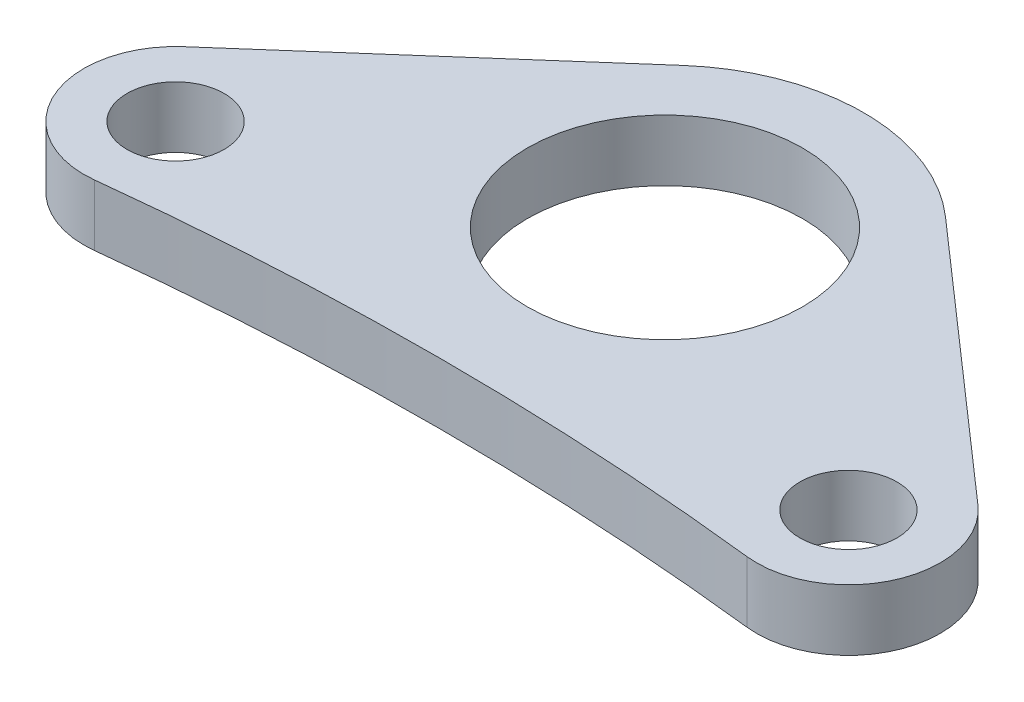
SolidWorks part; units mm, degrees
material "Plain Carbon Steel"
ref_plane "Front Plane" through (0, 0, 0) normal (0, 0, 1) x (1, 0, 0)
ref_plane "Top Plane" through (0, 0, 0) normal (0, 1, 0) x (1, 0, 0)
ref_plane "Right Plane" through (0, 0, 0) normal (1, 0, 0) x (0, 0, -1)
sketch "Sketch1" plane through (0, 0, 0) normal (0, 1, 0) x (1, 0, 0)
  line L0 (-41.2092, -8.7172) -> (-13.6158, 15.5086)
  line L1 (13.6158, 15.5086) -> (41.2092, -8.7172)
  circle A0 centre (0, 0) radius 14.2875
  arc A1 (-33.858, -25.3401) -> (-41.2092, -8.7172) centre (-34.925, -15.875) cw
  arc A2 (33.858, -25.3401) -> (41.2092, -8.7172) centre (34.925, -15.875) ccw
  arc A3 (-33.858, -25.3401) -> (33.858, -25.3401) centre (0, -325.6977) cw
  arc A4 (-13.6158, 15.5086) -> (13.6158, 15.5086) centre (0, 0) cw
  point P3 (-34.925, -15.875)
  point P4 (34.925, -15.875)
  dimension "D4" = 28.575
  dimension "D5" = 302.26
  dimension "D6" = 9.525
  dimension "D7" = 6.35
  dimension "D8" = 9.525
  dimension "D1" = 15.875
  dimension "D2" = 34.925
  dimension "D3" = 34.925
extrude "Boss-Extrude1" add sketch "Sketch1" along normal blind 6.35
hole_wizard "3/8 Clearance Hole1" positions "Sketch4" profile "Sketch3" hole size "3/8" standard "ANSI Inch" end condition through all
sketch "Sketch4" plane through (0, 6.35, 0) normal (0, 1, 0) x (1, 0, 0)
  point P0 (-34.925, -15.875)
  point P3 (34.925, -15.875)
sketch "Sketch3" plane through (-34.925, 6.35, 15.875) normal (1, 0, 0) x (0, 0, 1)
  line L0 (0, 0) -> (0, 6.35)
  line L1 (0, 6.35) -> (5.0419, 6.35)
  line L2 (5.0419, 6.35) -> (5.0419, 0)
  line L5 (5.0419, 0) -> (0, 0)
  line L11 (0, -6.35) -> (0, 107.95) construction
  dimension "Thru Hole Dia." = 10.0838
  dimension "Thru Hole Depth" = 6.35
